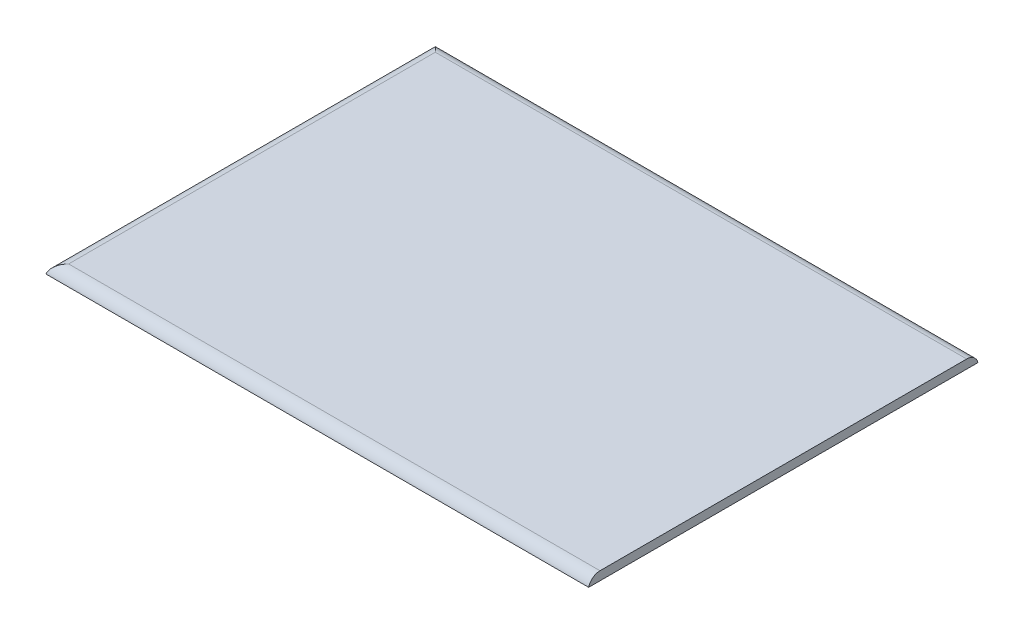
SolidWorks part; units mm, degrees
ref_plane "Front Plane" through (0, 0, 0) normal (0, 0, 1) x (1, 0, 0)
ref_plane "Top Plane" through (0, 0, 0) normal (0, 1, 0) x (1, 0, 0)
ref_plane "Right Plane" through (0, 0, 0) normal (1, 0, 0) x (0, 0, -1)
sketch "Sketch1" plane through (0, 0, 0) normal (0, 1, 0) x (1, 0, 0)
  line L1 (-46.5, 33.4) -> (46.5, 33.4)
  line L2 (-46.5, 33.4) -> (-46.5, -33.4)
  line L3 (-46.5, -33.4) -> (46.5, -33.4)
  line L4 (46.5, 33.4) -> (46.5, -33.4)
  point P4 (39.1262, -19.1117)
  point P5 (0, 33.4)
  point P7 (46.5, 0)
  dimension "D1" = 93
  dimension "D2" = 66.8
extrude "Boss-Extrude1" add sketch "Sketch1" along normal mid plane 2.5
fillet "Fillet1" radius 2 3 edges at (0, 1.25, -33.4) (-46.5, 1.25, 0) (0, 1.25, 33.4)
sketch "Sketch2" plane through (0, -1.25, 0) normal (0, -1, 0) x (1, 0, 0)
  line L1 (-46.5, 33.4) -> (46.5, 33.4)
  line L2 (-46.5, 33.4) -> (-46.5, -33.4)
  line L3 (-46.5, -33.4) -> (46.5, -33.4)
  line L4 (46.5, 33.4) -> (46.5, -33.4)
extrude "Cut-Extrude1" cut sketch "Sketch2" against normal blind 1
sketch "Sketch3" plane through (0, -0.25, 0) normal (0, -1, 0) x (1, 0, 0)
  line L0 (43.5, 30.4) -> (43.5, -30.4) construction
  line L1 (-43.5, -30.4) -> (43.5, -30.4) construction
  circle A0 centre (-43.5, 30.4) radius 1
  circle A1 centre (43.5, 30.4) radius 1
  circle A2 centre (43.5, -30.4) radius 1
  circle A3 centre (-43.5, -30.4) radius 1
  point P8 (43.5, 0)
  point P9 (0, -30.4)
  point P10 (-43.5, -30.4)
  dimension "D1" = 2
  dimension "D2" = 2
  dimension "D3" = 2
  dimension "D4" = 2
  dimension "D5" = 60.8
  dimension "D6" = 87
extrude "Cut-Extrude2" cut sketch "Sketch3" against normal blind 0.75
sketch "Sketch4" plane through (0, -0.25, 0) normal (0, -1, 0) x (1, 0, 0)
  line L0 (-37.55, 26.4865) -> (-37.55, 27.9365) construction
  line L1 (-46.4365, 33.3365) -> (46.5, 33.3365) construction
  line L2 (-37.55, 26.4865) -> (17.55, 26.4865) construction
  circle A0 centre (-37.55, 26.4865) radius 1.45
  circle A1 centre (17.55, 26.4865) radius 1.45
  circle A2 centre (17.55, -19.6135) radius 1.45
  circle A3 centre (-37.55, -19.6135) radius 1.45
  point P10 (-10, 26.4865)
  point P11 (-32.3114, 26.4865)
  dimension "D1" = 2.9
  dimension "D2" = 2.9
  dimension "D3" = 2.9
  dimension "D4" = 2.9
  dimension "D5" = 46.1
  dimension "D6" = 55.1
  dimension "D7" = 5.4
  dimension "D8" = 10
extrude "Boss-Extrude2" add sketch "Sketch4" along normal blind 5
sketch "Sketch5" plane through (0, -0.25, 0) normal (0, -1, 0) x (1, 0, 0)
  circle A0 centre (-37.55, 26.4865) radius 2.5
  circle A1 centre (17.55, 26.4865) radius 2.5
  circle A2 centre (17.55, -19.6135) radius 2.5
  circle A3 centre (-37.55, -19.6135) radius 2.5
  dimension "D1" = 5
  dimension "D2" = 5
  dimension "D3" = 5
  dimension "D4" = 5
extrude "Boss-Extrude3" add sketch "Sketch5" along normal blind 1.8
